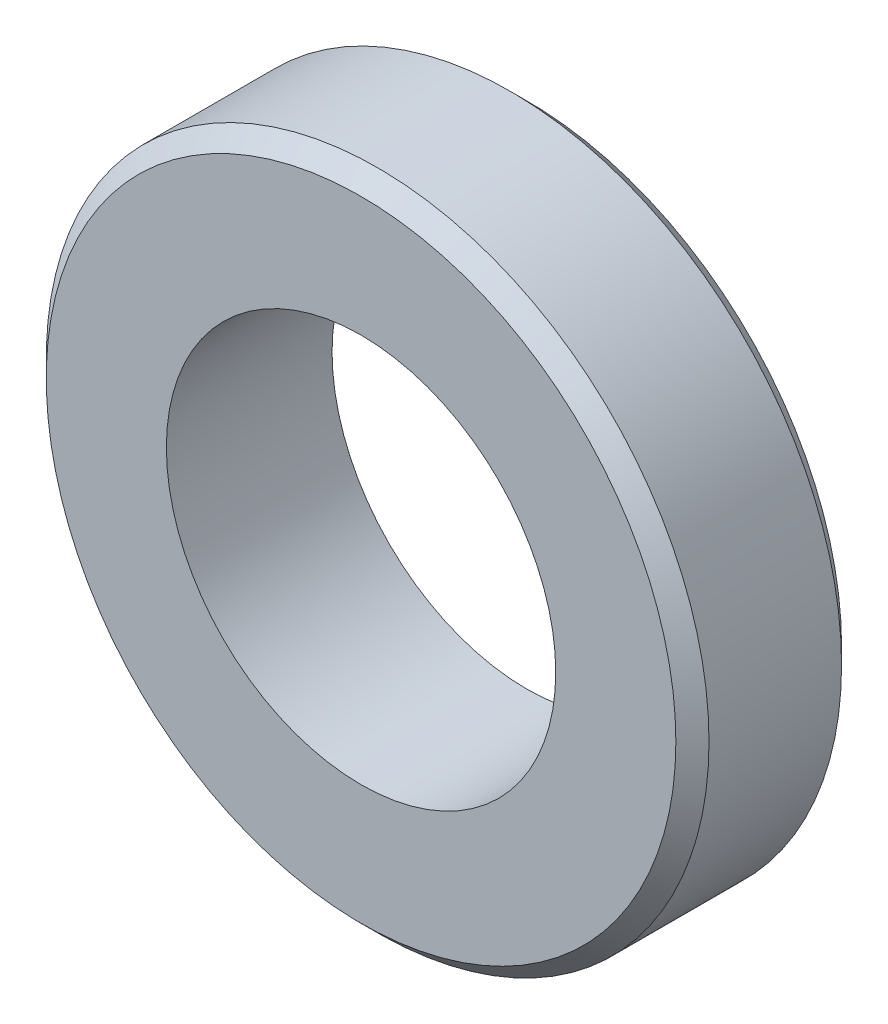
SolidWorks part; units mm, degrees
ref_plane "Front Plane" through (0, 0, 0) normal (0, 0, 1) x (1, 0, 0)
ref_plane "Top Plane" through (0, 0, 0) normal (0, 1, 0) x (1, 0, 0)
ref_plane "Right Plane" through (0, 0, 0) normal (1, 0, 0) x (0, 0, -1)
sketch "Sketch2" plane through (0, 0, 0) normal (0, 0, 1) x (1, 0, 0)
  circle A0 centre (0, 0) radius 23.5
  circle A1 centre (0, 0) radius 40
extrude "Boss-Extrude1" add sketch "Sketch2" along normal blind 20
chamfer "Chamfer1" distance 2 angle 45 2 edges at (40, 0, 20) (40, 0, 0)
